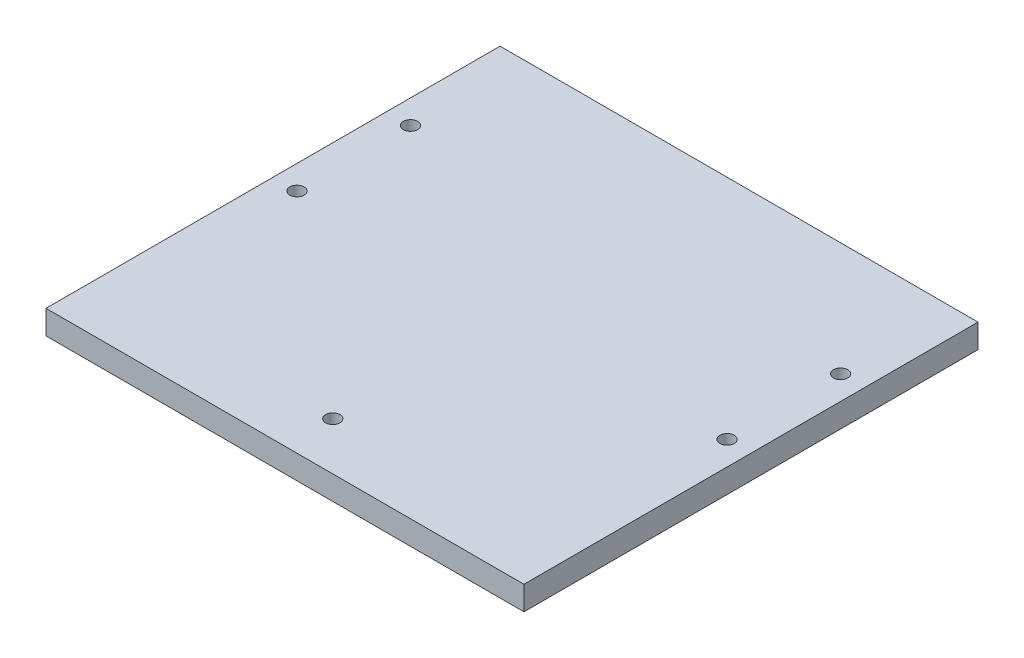
SolidWorks part; units mm, degrees
ref_plane "Front Plane" through (0, 0, 0) normal (0, 0, 1) x (1, 0, 0)
ref_plane "Top Plane" through (0, 0, 0) normal (0, 1, 0) x (1, 0, 0)
ref_plane "Right Plane" through (0, 0, 0) normal (1, 0, 0) x (0, 0, -1)
sketch "Sketch1" plane through (0, 0, 0) normal (0, 1, 0) x (1, 0, 0)
  line L1 (0, 0) -> (200, 0)
  line L2 (0, 0) -> (0, 190)
  line L3 (0, 190) -> (200, 190)
  line L4 (200, 0) -> (200, 190)
  dimension "D1" = 190
  dimension "D2" = 200
extrude "Boss-Extrude1" add sketch "Sketch1" along normal blind 10
sketch "Sketch2" plane through (0, 0, -190) normal (0, 0, -1) x (-1, 0, 0)
  line L0 (-200, 10) -> (0, 10) construction
  line L5 (-200, 0) -> (0, 0) construction
  line L6 (-138, 2) -> (-118, 2)
  line L11 (-62, 9) -> (-82, 9)
  line L12 (0, 10) -> (0, 0) construction
  line L13 (-20, 0) -> (-40, 0)
  line L14 (-20, 0) -> (-20, 10)
  line L15 (-20, 10) -> (-40, 10)
  line L16 (-40, 0) -> (-40, 10)
  line L17 (0, 10) -> (-100, 10) construction
  line L18 (-22, 8) -> (-38, 8)
  line L19 (-22, 8) -> (-22, 2)
  line L20 (-22, 2) -> (-38, 2)
  line L21 (-38, 8) -> (-38, 2)
  line L22 (-100, 10) -> (-100, -21.092) construction
  line L23 (-178, 2) -> (-162, 2)
  line L24 (-162, 8) -> (-162, 2)
  line L25 (-178, 8) -> (-162, 8)
  line L26 (-178, 8) -> (-178, 2)
  line L27 (-62, 9) -> (-62, 2)
  line L28 (-62, 2) -> (-82, 2)
  line L29 (-82, 9) -> (-82, 2)
  line L30 (-118, 9) -> (-118, 2)
  line L31 (-138, 9) -> (-118, 9)
  line L32 (-138, 9) -> (-138, 2)
  dimension "D1" = 20
  dimension "D2" = 22
  dimension "D3" = 20
  dimension "D4" = 20
  dimension "D5" = 2
  dimension "D6" = 2
  dimension "D7" = 2
  dimension "D8" = 2
  dimension "D9" = 1
  dimension "D10" = 2
  dimension "D11" = 7
  dimension "D12" = 2
  dimension "D13" = 1
  dimension "D14" = 7
  dimension "D15" = 2
  dimension "D16" = 18
  dimension "D17" = 62
extrude "Cut-Extrude1" cut sketch "Sketch2" against normal blind 10 contours L19 L18 L21 L20 | L27 L11 L29 L28 | L6 L30 L31 L32 | L23 L24 L25 L26
sketch "Sketch4" plane through (0, 0, 0) normal (0, -1, 0) x (-1, 0, 0)
  line L5 (0, 190) -> (0, 0) construction
  line L6 (-100, 190) -> (-100, 0) construction
  line L7 (-200, 190) -> (0, 190) construction
  line L8 (0, 0) -> (-200, 0) construction
  circle A2 centre (-10, 142.5) radius 3
  circle A3 centre (-10, 95) radius 3
  circle A4 centre (-190, 95) radius 3
  circle A5 centre (-190, 142.5) radius 3
  dimension "D2" = 6
  dimension "D3" = 6
  dimension "D4" = 142.5
  dimension "D5" = 95
  dimension "D6" = 10
  dimension "D1" = 95
  dimension "D7" = 142.5
  dimension "D9" = 10
extrude "Cut-Extrude2" cut sketch "Sketch4" against normal blind 10
sketch "Sketch5" plane through (0, 10, 0) normal (0, 1, 0) x (1, 0, 0)
  line L0 (100, 0) -> (100, 68.1384) construction
  line L2 (0, 0) -> (200, 0) construction
  line L3 (0, 0) -> (200, 0) construction
  circle A0 centre (100, 20) radius 3
  dimension "D1" = 6
  dimension "D2" = 20
extrude "Cut-Extrude3" cut sketch "Sketch5" against normal blind 10
